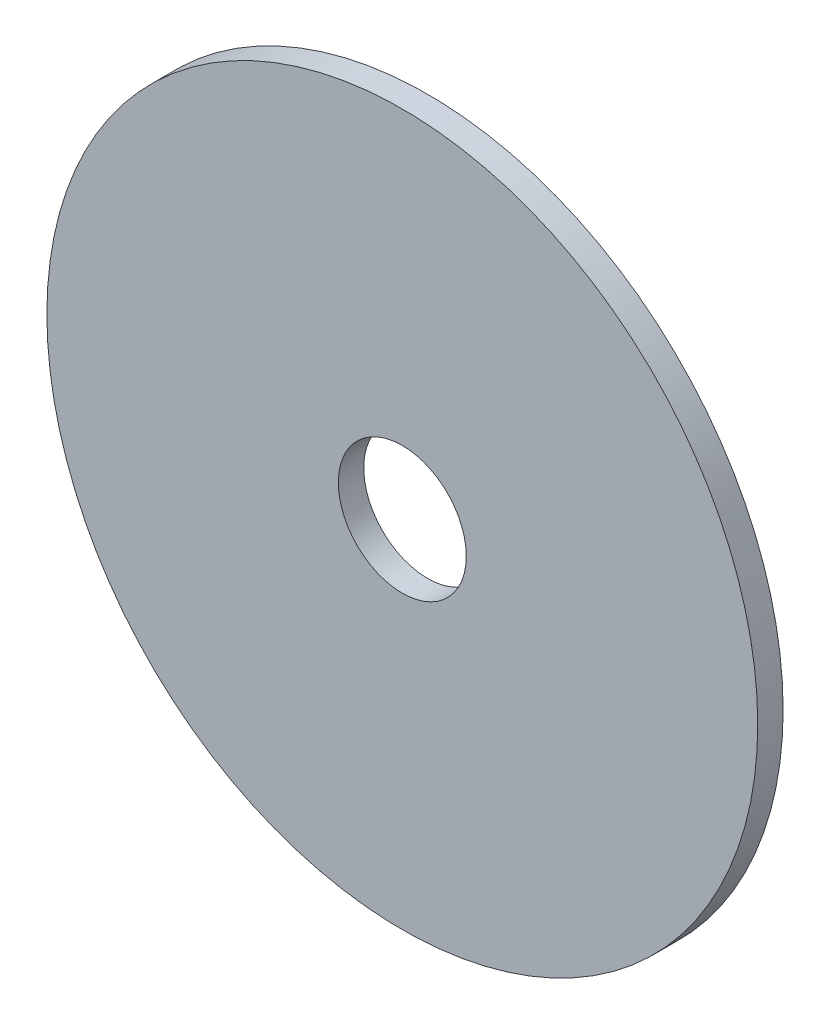
SolidWorks part; units mm, degrees
ref_plane "Front Plane" through (0, 0, 0) normal (0, 0, 1) x (1, 0, 0)
ref_plane "Top Plane" through (0, 0, 0) normal (0, 1, 0) x (1, 0, 0)
ref_plane "Right Plane" through (0, 0, 0) normal (1, 0, 0) x (0, 0, -1)
sketch "Sketch1" plane through (0, 0, 0) normal (0, 0, 1) x (1, 0, 0)
  line L0 (-22.225, 0) -> (22.225, 0) construction
  line L1 (-4, 0) -> (4, 0) construction
  circle A0 centre (0, 0) radius 4 construction
  circle A1 centre (0, 0) radius 22.225 construction
  point P8 (0, 0)
  point P9 (0, 22.225)
  point P11 (4, 0)
  dimension "ID" = 8
  dimension "OD" = 44.45
sketch "Sketch3" plane through (0, 0, 0) normal (0, 0, 1) x (1, 0, 0)
  circle A0 centre (0, 0) radius 4
  circle A1 centre (0, 0) radius 22.225
extrude "Boss-Extrude1" add sketch "Sketch3" along normal blind 1.5875
equation "\"1.375n\"=1.5"
